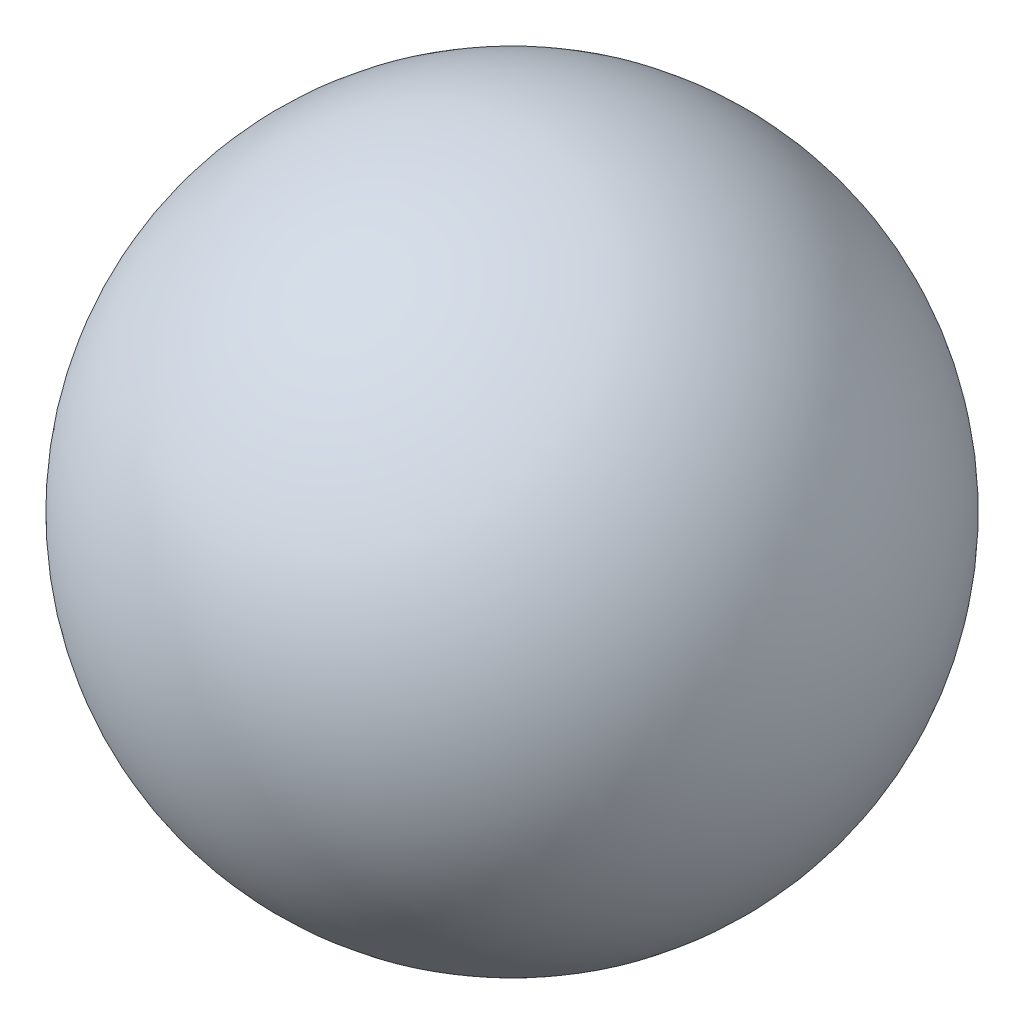
SolidWorks part; units mm, degrees
material "PET"
ref_plane "Front Plane" through (0, 0, 0) normal (0, 0, 1) x (1, 0, 0)
ref_plane "Top Plane" through (0, 0, 0) normal (0, 1, 0) x (1, 0, 0)
ref_plane "Right Plane" through (0, 0, 0) normal (1, 0, 0) x (0, 0, -1)
sketch "Sketch1" plane through (0, 0, 0) normal (0, 0, 1) x (1, 0, 0)
  line L0 (0, 20) -> (0, -20) construction
  circle A0 centre (0, 0) radius 20
  dimension "D1" = 40
revolve "Revolve2" add sketch "Sketch1" angle 360 about L0
shell "Shell1" thickness 0.4
